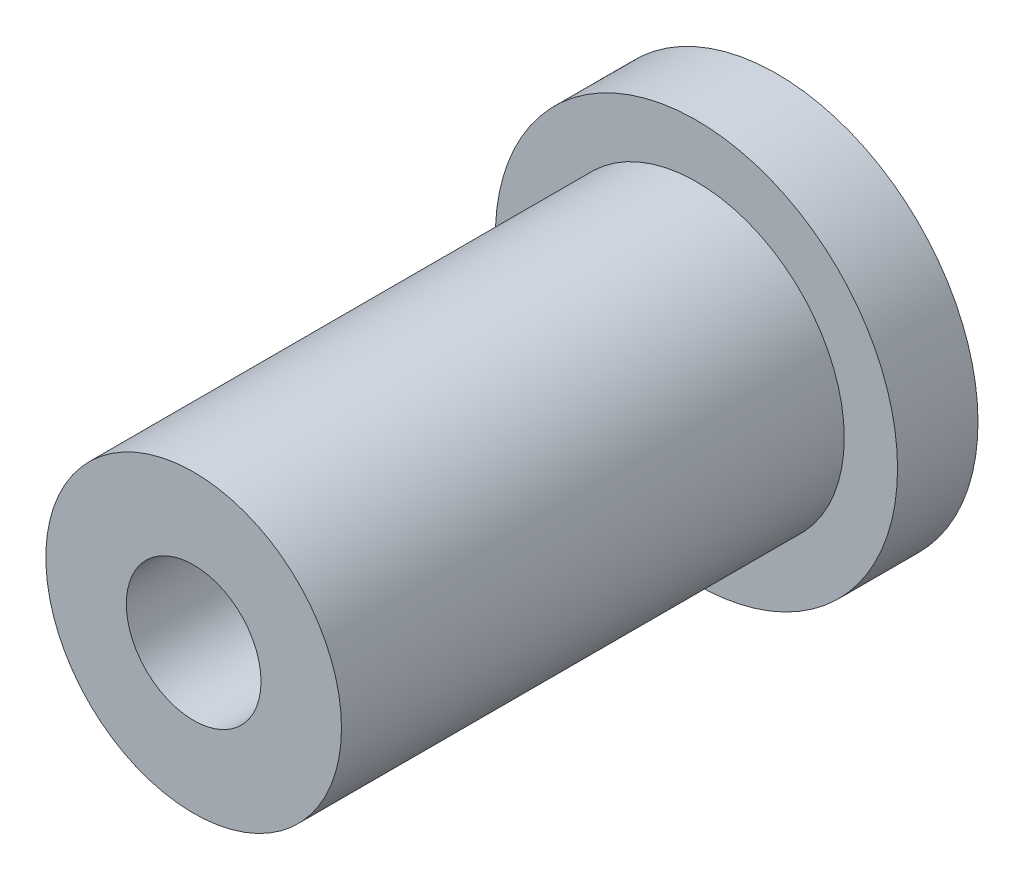
SolidWorks part; units mm, degrees
ref_plane "前视基准面" through (0, 0, 0) normal (0, 0, 1) x (1, 0, 0)
ref_plane "上视基准面" through (0, 0, 0) normal (0, 1, 0) x (1, 0, 0)
ref_plane "右视基准面" through (0, 0, 0) normal (1, 0, 0) x (0, 0, -1)
other "Configuration Table"
sketch "草图1" plane through (0, 0, 0) normal (0, 0, 1) x (1, 0, 0)
  circle A0 centre (0, 0) radius 10
  dimension "D1" = 20
extrude "拉伸-薄壁1" add sketch "草图1" along normal blind 4 thin thin type one direction reverse wall 6
sketch "草图2" plane through (0, 0, 4) normal (0, 0, 1) x (1, 0, 0)
  circle A0 centre (0, 0) radius 7.35
  dimension "D1" = 14.7
extrude "拉伸-薄壁2" add sketch "草图2" along normal blind 25 thin thin type one direction reverse wall 4
